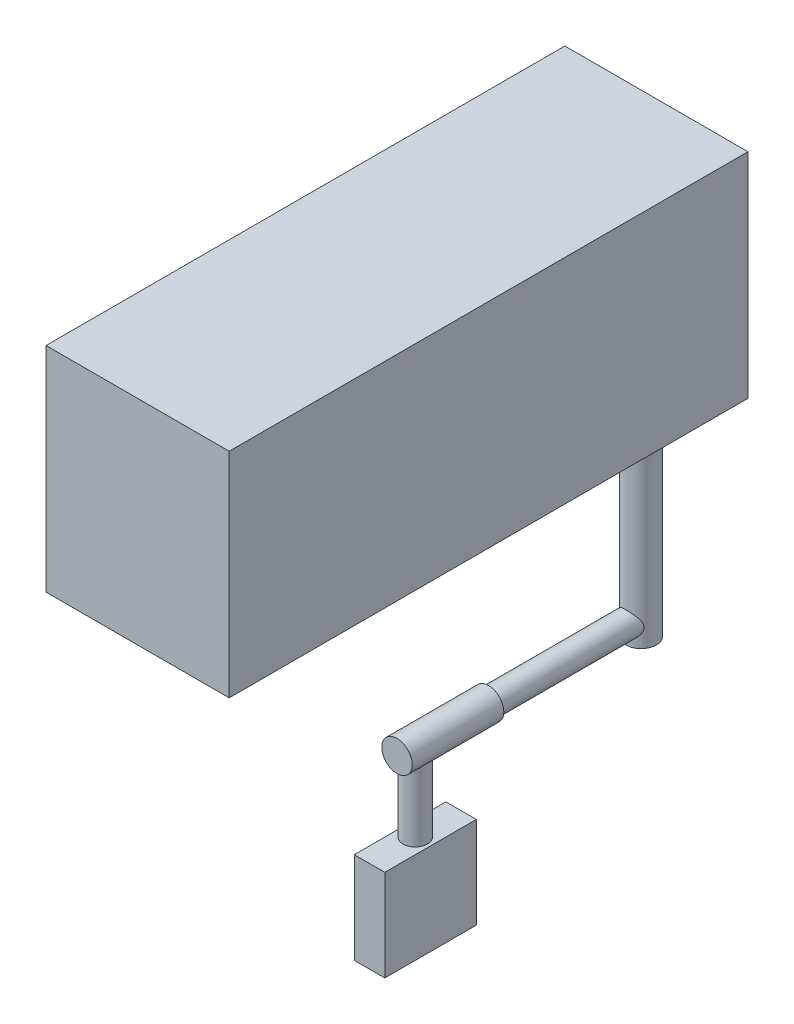
SolidWorks part; units mm, degrees
ref_plane "Alzado" through (0, 0, 0) normal (0, 0, 1) x (1, 0, 0)
ref_plane "Planta" through (0, 0, 0) normal (0, 1, 0) x (1, 0, 0)
ref_plane "Vista lateral" through (0, 0, 0) normal (1, 0, 0) x (0, 0, -1)
sketch "Croquis5" plane through (0, 0, 0) normal (0, 1, 0) x (1, 0, 0)
  circle A0 centre (0, 0) radius 5
  dimension "D1" = 10
extrude "Saliente-Extruir2" add sketch "Croquis5" along normal blind 70
sketch "Croquis6" plane through (0, 0, 0) normal (0, 0, 1) x (1, 0, 0)
  circle A0 centre (0, 6) radius 4
  dimension "D1" = 8
  dimension "D2" = 6
extrude "Saliente-Extruir3" add sketch "Croquis6" along normal blind 50
sketch "Croquis7" plane through (0, 0, 50) normal (0, 0, 1) x (1, 0, 0)
  circle A0 centre (0, 6) radius 5
  dimension "D1" = 10
extrude "Saliente-Extruir4" add sketch "Croquis7" along normal blind 30
sketch "Croquis8" plane through (0, 0, 0) normal (0, 1, 0) x (1, 0, 0)
  line L0 (-5, -80) -> (5, -80) construction
  circle A0 centre (0, -74) radius 4
  dimension "D1" = 8
  dimension "D2" = 6
extrude "Saliente-Extruir5" add sketch "Croquis8" against normal blind 20 and the other way blind 5
sketch "Croquis10" plane through (0, -20, 0) normal (0, -1, 0) x (1, 0, 0)
  line L0 (-5, 74) -> (0, 74) construction
  line L1 (-5, 89) -> (5, 89)
  line L2 (-5, 89) -> (-5, 59)
  line L3 (-5, 59) -> (5, 59)
  line L4 (5, 89) -> (5, 59)
  point P4 (0, 59)
  dimension "D1" = 10
  dimension "D2" = 30
extrude "Saliente-Extruir6" add sketch "Croquis10" along normal blind 30
sketch "Croquis11" plane through (0, 70, 0) normal (0, 1, 0) x (1, 0, 0)
  line L1 (-40, 15) -> (20, 15)
  line L2 (-40, 15) -> (-40, -155)
  line L3 (-40, -155) -> (20, -155)
  line L4 (20, 15) -> (20, -155)
  dimension "D1" = 60
  dimension "D2" = 170
  dimension "D3" = 20
  dimension "D4" = 15
extrude "Saliente-Extruir7" add sketch "Croquis11" along normal blind 70
